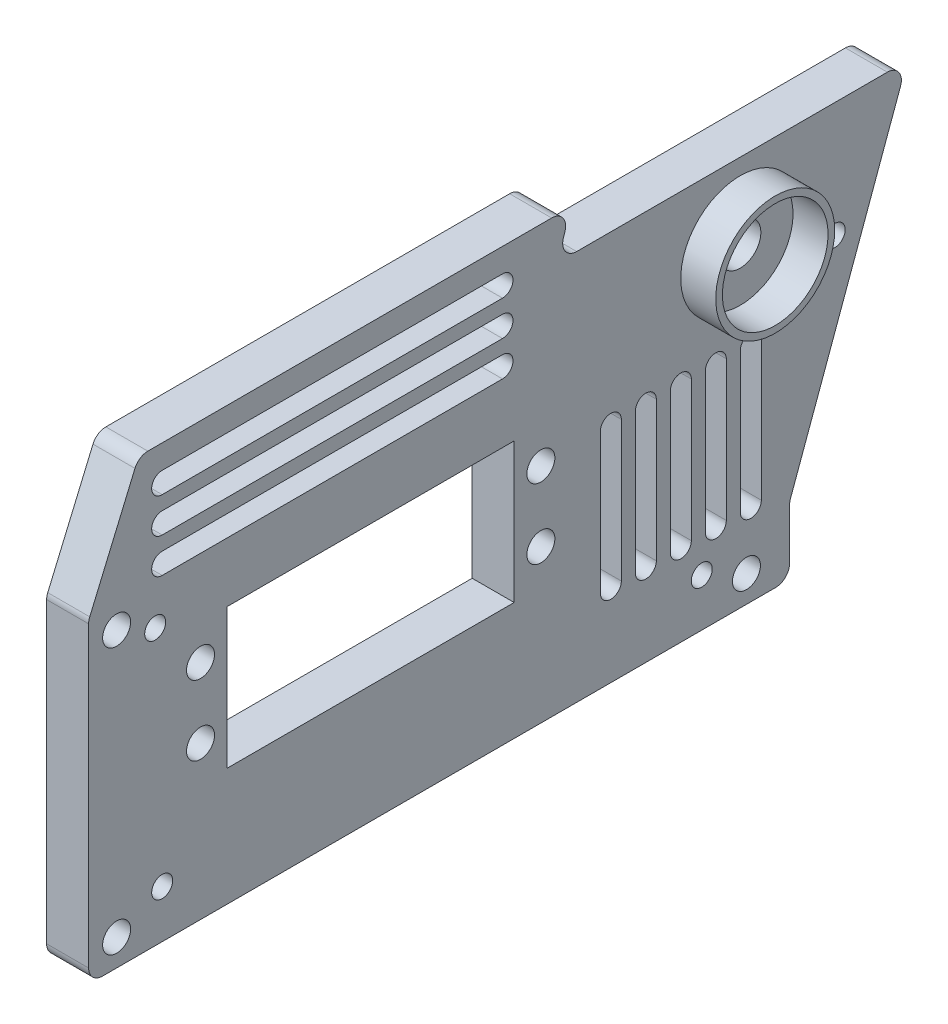
SolidWorks part; units mm, degrees
ref_plane "前视基准面" through (0, 0, 0) normal (0, 0, 1) x (1, 0, 0)
ref_plane "上视基准面" through (0, 0, 0) normal (0, 1, 0) x (1, 0, 0)
ref_plane "右视基准面" through (0, 0, 0) normal (1, 0, 0) x (0, 0, -1)
sketch "草图1" plane through (0, 0, 0) normal (1, 0, 0) x (0, 0, -1)
  line L33 (-58.1085, -35) -> (42.0593, -35)
  line L34 (42.0593, -35) -> (42.0593, -30.6775)
  line L35 (-58.1085, 10) -> (-50.9678, 26.7336)
  line L46 (-58.1085, 10) -> (-58.1085, -35)
  line L47 (-50.9678, 26.7336) -> (-8.1085, 26.7336)
  line L50 (10.8022, 26.7336) -> (-8.1085, 26.7336)
  line L56 (10.8022, 26.7336) -> (8.8845, 20.7944)
  line L57 (53.8845, 20.7944) -> (8.8845, 20.7944)
  line L59 (53.8845, 20.7944) -> (58.8845, 20.7944)
  line L60 (58.8845, 20.7944) -> (52.2202, 2.5021)
  line L61 (52.2202, 2.5021) -> (42.0593, -25.3878)
  line L62 (42.0593, -25.3878) -> (42.0593, -30.6775)
  dimension "D1" = 100.1678
  dimension "D2" = 5
extrude "凸台-拉伸1" add sketch "草图1" along normal blind 6
sketch "草图2" plane through (0, 0, 0) normal (1, 0, 0) x (0, 0, -1)
  line L0 (-17.8023, 6.0643) -> (-17.8023, -21.9388) construction
  line L1 (35, 10) -> (-7.8023, -8.1717) construction
  line L2 (-58.1085, -35) -> (42.0593, -35) construction
  line L4 (-17.8023, 1.8283) -> (-38.3023, 1.8283)
  line L9 (-38.3023, 1.8283) -> (-38.3023, -18.1717)
  line L10 (-38.3023, -18.1717) -> (-17.8023, -18.1717)
  line L11 (-17.8023, -18.1717) -> (2.6977, -18.1717)
  line L12 (2.6977, -18.1717) -> (2.6977, 1.8283)
  line L13 (2.6977, 1.8283) -> (-17.8023, 1.8283)
  circle A1 centre (35, 10) radius 2.5 construction
  circle A6 centre (6.5127, -3.1717) radius 2
  circle A7 centre (6.5127, -13.1717) radius 2
  circle A8 centre (-42.1173, -13.1717) radius 2
  circle A9 centre (-42.1173, -3.1717) radius 2
  dimension "D2" = 10
  dimension "D1" = 5
  dimension "D10" = 45
  dimension "D12" = 4
  dimension "D11" = 4
  dimension "D3" = 46.5
  dimension "D4" = 20.5
  dimension "D13" = 20.5
extrude "切除-拉伸1" cut sketch "草图2" along normal blind 10
sketch "草图4" plane through (6, 0, 0) normal (1, 0, 0) x (0, 0, -1)
  line L0 (6.5127, -3.1717) -> (6.5127, 6.8283) construction
  line L3 (-48.5978, 4.3283) -> (48.5022, 4.3283) construction
  line L6 (35, 15) -> (25, 15) construction
  line L7 (35, 15) -> (49, 15) construction
  line L9 (35, 5) -> (21, 5) construction
  line L10 (35, 5) -> (45, 5) construction
  line L11 (49, 15) -> (45, 5) construction
  circle A10 centre (35, 10) radius 2.5 construction
  circle A17 centre (-48.5978, 4.3283) radius 1.5
  circle A19 centre (48.5022, 4.3283) radius 1.5
  dimension "D4" = 3
  dimension "D5" = 5
  dimension "D2" = 97.1
  dimension "D3" = 3
  dimension "D8" = 5
  dimension "D9" = 14
  dimension "D1" = 10
  dimension "D6" = 10
  dimension "D7" = 14
  dimension "D10" = 10
extrude "切除-拉伸2" cut sketch "草图4" against normal blind 6
sketch "草图5" plane through (6, 0, 0) normal (1, 0, 0) x (0, 0, -1)
  circle A1 centre (35, 10) radius 8.5
  dimension "D2" = 17
sketch "草图7" plane through (6, 0, 0) normal (1, 0, 0) x (0, 0, -1)
  line L0 (-47.5978, 6.8283) -> (-47.5978, -28.1717)
  line L1 (-58.1085, 6.8283) -> (-54.1085, 6.8283)
  line L2 (-58.1085, 10) -> (-58.1085, -35) construction
  line L3 (-54.1085, 6.8283) -> (-54.1085, -31.1717)
  line L4 (-54.1085, -31.1717) -> (35.8915, -31.1717)
  line L5 (6.5127, -3.1717) -> (16.5127, -3.1717) construction
  line L6 (15.0127, -3.1717) -> (15.0127, -23.1717)
  line L7 (-47.5978, 18.3283) -> (1.0322, 18.3283)
  line L8 (-47.5978, 23.3283) -> (1.0322, 23.3283)
  line L9 (-47.5978, 20.3283) -> (1.0322, 20.3283)
  line L10 (-47.5978, 15.3283) -> (1.0322, 15.3283)
  line L11 (-47.5978, 13.3283) -> (1.0322, 13.3283)
  line L12 (-47.5978, 10.3283) -> (1.0322, 10.3283)
  line L13 (-23.2828, 28.3114) -> (-23.2828, 6.1847) construction
  line L14 (16.5127, -3.1717) -> (21.5127, -3.1717) construction
  line L15 (21.5127, -3.1717) -> (26.5127, -3.1717) construction
  line L16 (26.5127, -3.1717) -> (31.5127, -3.1717) construction
  line L17 (12.7048, -15.6717) -> (36.6303, -15.6717) construction
  line L26 (31.5127, -3.1717) -> (36.5127, -3.1717) construction
  line L27 (36.5127, -3.1717) -> (36.5127, -23.1717) construction
  line L28 (35.0127, -3.1717) -> (35.0127, -23.1717)
  line L29 (38.0127, -23.1717) -> (38.0127, -3.1717)
  line L30 (-47.5978, -28.1717) -> (29.5022, -28.1717) construction
  line L31 (18.0127, -3.1717) -> (18.0127, -23.1717)
  line L33 (20.0127, -3.1717) -> (20.0127, -23.1717)
  line L34 (23.0127, -3.1717) -> (23.0127, -23.1717)
  line L35 (25.0127, -3.1717) -> (25.0127, -23.1717)
  line L36 (28.0127, -3.1717) -> (28.0127, -23.1717)
  line L37 (30.0127, -3.1717) -> (30.0127, -23.1717)
  line L38 (33.0127, -3.1717) -> (33.0127, -23.1717)
  circle A0 centre (-47.5978, -28.1717) radius 1.5
  arc A9 (-47.5978, 23.3283) -> (-47.5978, 20.3283) centre (-47.5978, 21.8283) ccw
  arc A10 (-47.5978, 10.3283) -> (-47.5978, 13.3283) centre (-47.5978, 11.8283) cw
  arc A11 (-47.5978, 18.3283) -> (-47.5978, 15.3283) centre (-47.5978, 16.8283) ccw
  arc A12 (1.0322, 10.3283) -> (1.0322, 13.3283) centre (1.0322, 11.8283) ccw
  arc A13 (1.0322, 18.3283) -> (1.0322, 15.3283) centre (1.0322, 16.8283) cw
  arc A14 (1.0322, 23.3283) -> (1.0322, 20.3283) centre (1.0322, 21.8283) cw
  circle A15 centre (-54.1085, 6.8283) radius 2
  circle A16 centre (-54.1085, -31.1717) radius 2
  circle A17 centre (35.8915, -31.1717) radius 2
  circle A18 centre (16.5127, -3.1717) radius 1.5 construction
  circle A19 centre (21.5127, -3.1717) radius 1.5 construction
  circle A20 centre (26.5127, -3.1717) radius 1.5 construction
  circle A21 centre (31.5127, -3.1717) radius 1.5 construction
  arc A22 (18.0127, -3.1717) -> (15.0127, -3.1717) centre (16.5127, -3.1717) ccw
  arc A23 (20.0127, -3.1717) -> (23.0127, -3.1717) centre (21.5127, -3.1717) cw
  arc A24 (25.0127, -3.1717) -> (28.0127, -3.1717) centre (26.5127, -3.1717) cw
  arc A25 (30.0127, -3.1717) -> (33.0127, -3.1717) centre (31.5127, -3.1717) cw
  circle A30 centre (36.5127, -3.1717) radius 1.5 construction
  circle A31 centre (36.5127, -23.1717) radius 1.5 construction
  arc A32 (35.0127, -3.1717) -> (38.0127, -3.1717) centre (36.5127, -3.1717) cw
  arc A33 (38.0127, -23.1717) -> (35.0127, -23.1717) centre (36.5127, -23.1717) cw
  arc A34 (18.0127, -23.1717) -> (15.0127, -23.1717) centre (16.5127, -23.1717) cw
  arc A35 (20.0127, -23.1717) -> (23.0127, -23.1717) centre (21.5127, -23.1717) ccw
  arc A36 (25.0127, -23.1717) -> (28.0127, -23.1717) centre (26.5127, -23.1717) ccw
  arc A37 (30.0127, -23.1717) -> (33.0127, -23.1717) centre (31.5127, -23.1717) ccw
  circle A38 centre (29.5022, -28.1717) radius 1.5
  point P63 (30.0127, -15.6717)
  point P69 (33.0127, -15.6717)
  point P70 (28.0127, -15.6717)
  point P71 (25.0127, -15.6717)
  point P73 (23.0127, -15.6717)
  point P75 (20.0127, -15.6717)
  point P76 (18.0127, -15.6717)
  point P77 (15.0127, -15.6717)
  dimension "D3" = 3
  dimension "D11" = 4
  dimension "D12" = 38
  dimension "D13" = 4
  dimension "D14" = 90
  dimension "D15" = 4
  dimension "D16" = 5
  dimension "D17" = 5
  dimension "D18" = 3
  dimension "D19" = 3
  dimension "D20" = 3
  dimension "D21" = 3
  dimension "D22" = 5
  dimension "D23" = 3
  dimension "D25" = 3
  dimension "D26" = 77.1
  dimension "D27" = 3
  dimension "D1" = 35
  dimension "D5" = 5
  dimension "D6" = 4
  dimension "D7" = 5
  dimension "D8" = 5
  dimension "D9" = 10
  dimension "D10" = 5
  dimension "D24" = 20
extrude "切除-拉伸3" cut sketch "草图7" against normal blind 6
extrude "凸台-拉伸4" add sketch "草图5" along normal blind 5
sketch "草图14" plane through (11, 0, 0) normal (1, 0, 0) x (0, 0, -1)
  circle A0 centre (35, 10) radius 7.55
  dimension "D1" = 15.1
extrude "切除-拉伸8" cut sketch "草图14" against normal blind 5
sketch "草图15" plane through (6, 0, 0) normal (1, 0, 0) x (0, 0, -1)
  circle A0 centre (35, 10) radius 2.95
  dimension "D1" = 5.9
extrude "切除-拉伸9" cut sketch "草图15" against normal blind 6
fillet "圆角1" radius 2 8 edges at (3, 10, 58.1085) (3, -35, 58.1085) (3, -35, -42.0593) (3, -25.3878, -42.0593) (3, 20.7944, -58.8845) (3, 20.7944, -8.8845) (3, 26.7336, -10.8022) (3, 26.7336, 50.9678)
